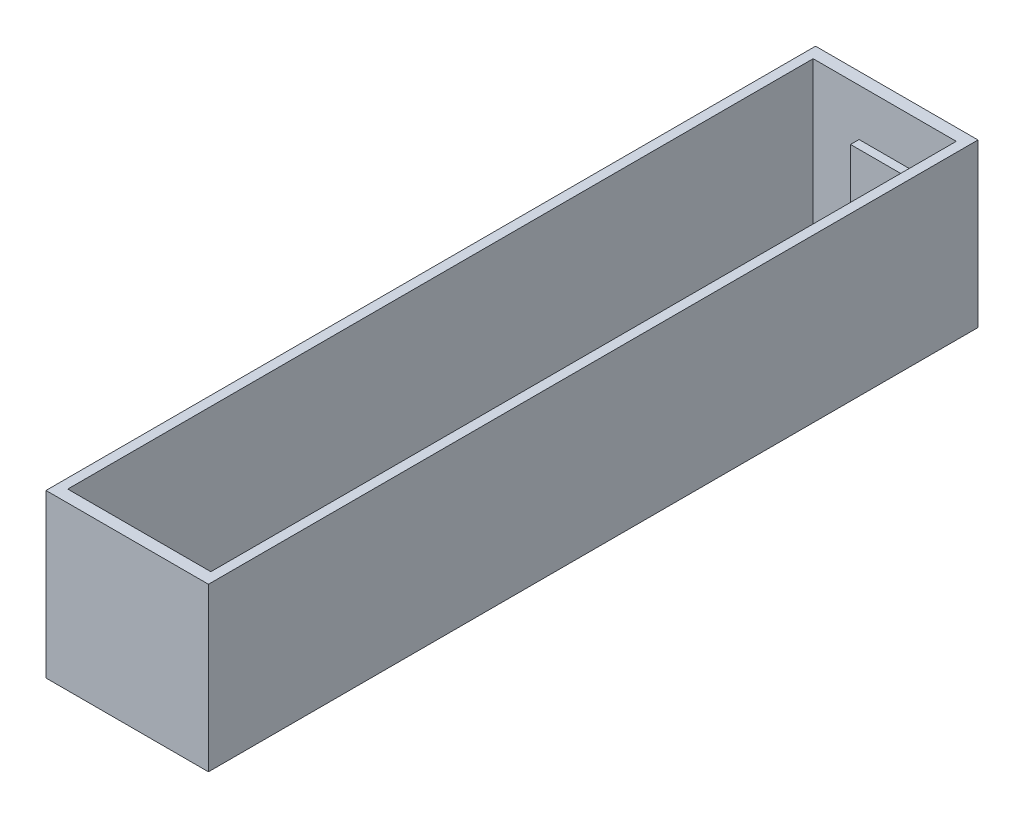
SolidWorks part; units mm, degrees
ref_plane "Front Plane" through (0, 0, 0) normal (0, 0, 1) x (1, 0, 0)
ref_plane "Top Plane" through (0, 0, 0) normal (0, 1, 0) x (1, 0, 0)
ref_plane "Right Plane" through (0, 0, 0) normal (1, 0, 0) x (0, 0, -1)
sketch "Sketch1" plane through (0, 0, 0) normal (0, 1, 0) x (1, 0, 0)
  line L1 (-13.0999, 76.8013) -> (5.9001, 76.8013)
  line L2 (-13.0999, 76.8013) -> (-13.0999, -13.1987)
  line L3 (-13.0999, -13.1987) -> (5.9001, -13.1987)
  line L4 (5.9001, 76.8013) -> (5.9001, -13.1987)
  dimension "D1" = 19
  dimension "D2" = 90
extrude "Boss-Extrude2" add sketch "Sketch1" along normal blind 19
sketch "Sketch2" plane through (0, 19, 0) normal (0, 1, 0) x (1, 0, 0)
  line L0 (5.9001, 76.8013) -> (-13.0999, 76.8013) construction
  line L1 (-11.9699, 75.3913) -> (4.7701, 75.3913)
  line L2 (-11.9699, 75.3913) -> (-11.9699, -11.7887)
  line L3 (-11.9699, -11.7887) -> (4.7701, -11.7887)
  line L4 (4.7701, 75.3913) -> (4.7701, -11.7887)
  line L5 (-13.0999, -13.1987) -> (5.9001, -13.1987) construction
  line L6 (5.9001, -13.1987) -> (5.9001, 76.8013) construction
  line L7 (-13.0999, 76.8013) -> (-13.0999, -13.1987) construction
  dimension "D1" = 1.41
  dimension "D2" = 1.41
  dimension "D3" = 1.13
  dimension "D4" = 1.13
extrude "Cut-Extrude1" cut sketch "Sketch2" against normal blind 17
sketch "Sketch3" plane through (0, 0, 11.7887) normal (0, 0, -1) x (-1, 0, 0)
  line L0 (11.9699, 2) -> (-4.7701, 2) construction
  line L1 (6.5999, 7.5) -> (0.5999, 7.5)
  line L2 (6.5999, 7.5) -> (6.5999, 13.5)
  line L3 (6.5999, 13.5) -> (0.5999, 13.5)
  line L4 (0.5999, 7.5) -> (0.5999, 13.5)
  line L7 (11.9699, 2) -> (11.9699, 19) construction
  dimension "D1" = 6
  dimension "D2" = 6
  dimension "D3" = 5.37
  dimension "D4" = 5.5
sketch "Sketch5" plane through (0, 0, -75.3913) normal (0, 0, 1) x (1, 0, 0)
  line L0 (-11.9699, 2) -> (-11.9699, 19) construction
  line L1 (-6.5999, 13.5) -> (-0.5999, 13.5)
  line L2 (-6.5999, 13.5) -> (-6.5999, 7.5)
  line L3 (-6.5999, 7.5) -> (-0.5999, 7.5)
  line L4 (-0.5999, 13.5) -> (-0.5999, 7.5)
  line L7 (4.7701, 2) -> (-11.9699, 2) construction
  dimension "D1" = 6
  dimension "D2" = 6
  dimension "D3" = 5.37
  dimension "D4" = 5.5
extrude "Boss-Extrude4" add sketch "Sketch3" along normal blind 1 contours L2 L1 L4 L3
extrude "Boss-Extrude5" add sketch "Sketch5" along normal blind 1
